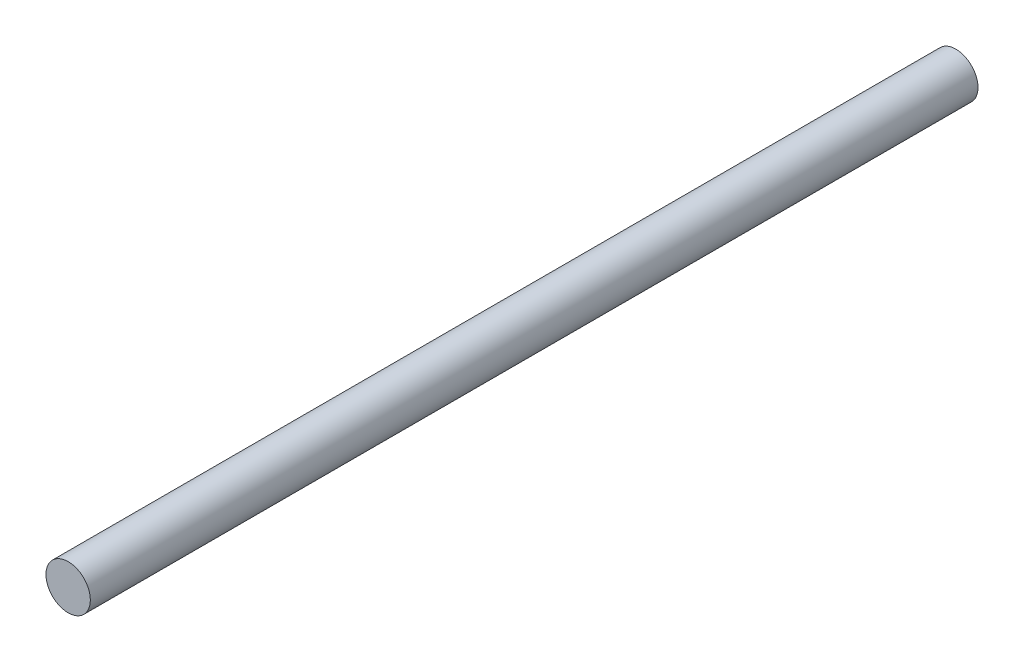
SolidWorks part; units mm, degrees
ref_plane "Front Plane" through (0, 0, 0) normal (0, 0, 1) x (1, 0, 0)
ref_plane "Top Plane" through (0, 0, 0) normal (0, 1, 0) x (1, 0, 0)
ref_plane "Right Plane" through (0, 0, 0) normal (1, 0, 0) x (0, 0, -1)
sketch "Sketch1" plane through (0, 0, 0) normal (0, 0, 1) x (1, 0, 0)
  circle A0 centre (0, 0) radius 0.75
  dimension "D1" = 1.5
extrude "Boss-Extrude1" add sketch "Sketch1" along normal blind 30
